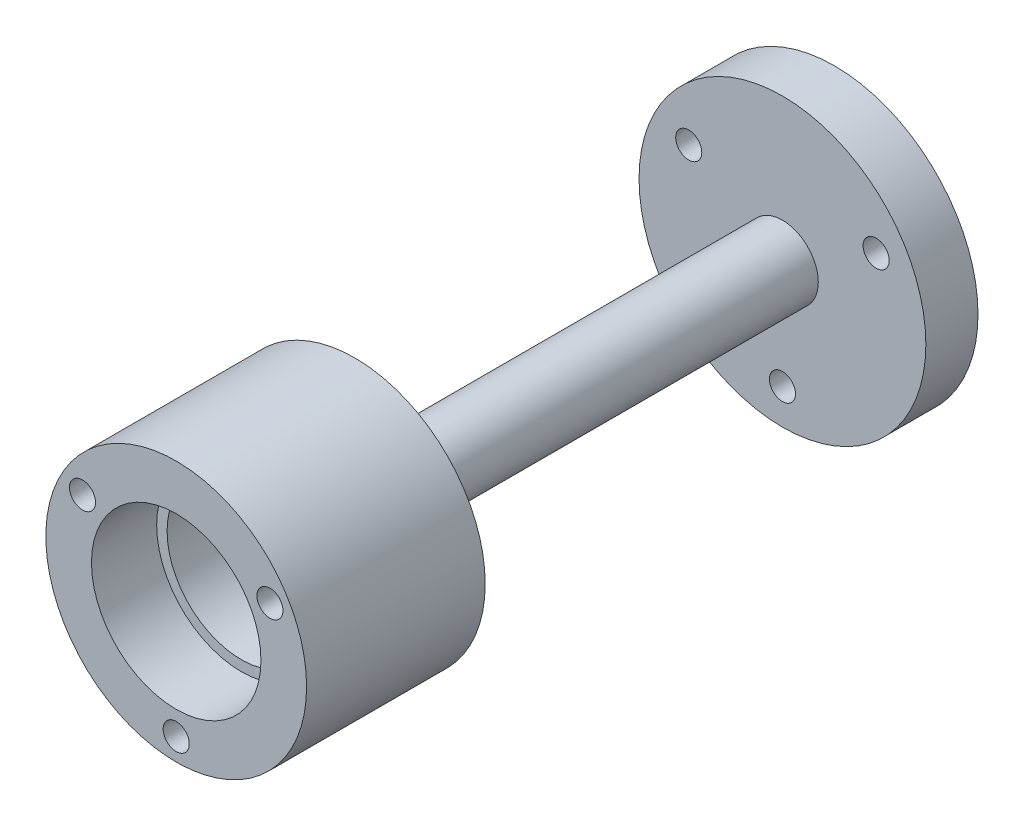
SolidWorks part; units mm, degrees
material "AISI 4340 Steel, normalized"
ref_plane "Front Plane" through (0, 0, 0) normal (0, 0, 1) x (1, 0, 0)
ref_plane "Top Plane" through (0, 0, 0) normal (0, 1, 0) x (1, 0, 0)
ref_plane "Right Plane" through (0, 0, 0) normal (1, 0, 0) x (0, 0, -1)
sketch "Sketch1" plane through (0, 0, 0) normal (0, 0, 1) x (1, 0, 0)
  circle A0 centre (0, 0) radius 11
extrude "Mounting_Flange" add sketch "Sketch1" along normal blind 4 from offset 4
sketch "Sketch2" plane through (0, 0, 0) normal (0, 0, 1) x (1, 0, 0)
  circle A0 centre (0, 0) radius 2.75
extrude "D5p5_Central_Post" add sketch "Sketch2" along normal blind 32.81
sketch "Sketch3" plane through (0, 0, 0) normal (0, 0, 1) x (1, 0, 0)
  circle A0 centre (0, 0) radius 10
extrude "Closed_Floor_Below_Shaft_Nose" add sketch "Sketch3" along normal blind 2.2 from offset 32.8
sketch "Sketch4" plane through (0, 0, 0) normal (0, 0, 1) x (1, 0, 0)
  circle A0 centre (0, 0) radius 10
  circle A1 centre (0, 0) radius 5.7
extrude "Shaft_And_Clip_Clearance" add sketch "Sketch4" along normal blind 6.5 from offset 35
sketch "Sketch5" plane through (0, 0, 0) normal (0, 0, 1) x (1, 0, 0)
  circle A0 centre (0, 0) radius 10
  circle A1 centre (0, 0) radius 6.5
extrude "Lower_686ZZ_Seat" add sketch "Sketch5" along normal blind 5 from offset 41.5
sketch "Sketch6" plane through (0, 0, -4) normal (0, 0, -1) x (-1, 0, 0)
  circle A0 centre (-7.188, 4.15) radius 1
  circle A1 centre (7.188, 4.15) radius 1
  circle A2 centre (0, -8.3) radius 1
extrude "Base_Three_M2_Through_Thread_Major_Envelopes" cut sketch "Sketch6" against normal blind 4.01
sketch "Sketch7" plane through (0, 0, 46.5) normal (0, 0, 1) x (1, 0, 0)
  circle A0 centre (7.188, 4.15) radius 1
  circle A1 centre (-7.188, 4.15) radius 1
  circle A2 centre (0, -8.3) radius 1
extrude "Top_Cap_Three_M2_Blind_Thread_Major_Envelopes" cut sketch "Sketch7" against normal blind 4.3
